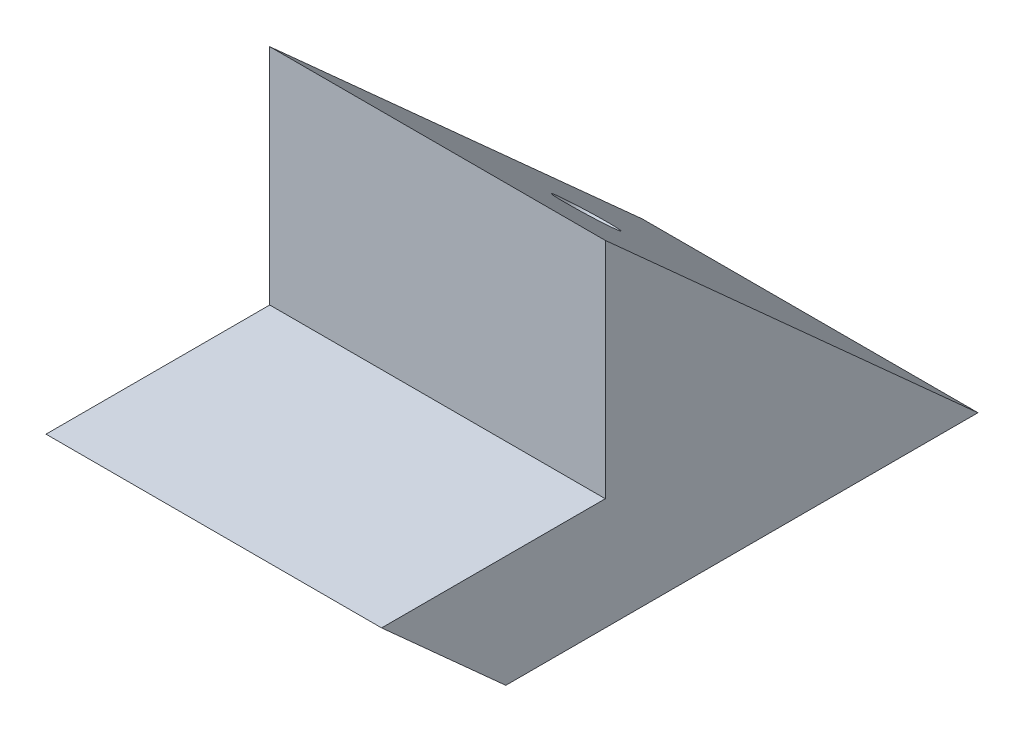
SolidWorks part; units mm, degrees
ref_plane "Front Plane" through (0, 0, 0) normal (0, 0, 1) x (1, 0, 0)
ref_plane "Top Plane" through (0, 0, 0) normal (0, 1, 0) x (1, 0, 0)
ref_plane "Right Plane" through (0, 0, 0) normal (1, 0, 0) x (0, 0, -1)
sketch "Esquisse1" plane through (0, 0, 0) normal (1, 0, 0) x (0, 0, -1)
  line L0 (0, 0) -> (33.3184, -30)
  line L1 (33.3184, -30) -> (-8.8939, -30)
  line L2 (-8.8939, -30) -> (-20, -20)
  line L3 (-20, -20) -> (0, -20)
  line L4 (0, -20) -> (0, 0)
  dimension "D1" = 42
  dimension "D2" = 42
  dimension "D3" = 20
  dimension "D4" = 20
  dimension "D5" = 10
extrude "Boss.-Extru.1" add sketch "Esquisse1" along normal blind 30
sketch "Esquisse2" plane through (0, 0, 0) normal (0, 0.7431, -0.6691) x (1, 0, 0)
  line L0 (15, 0) -> (15, 44.8343) construction
  line L1 (30, 0) -> (0, 0) construction
  line L2 (30, 44.8343) -> (0, 44.8343) construction
  line L3 (30, 22.4171) -> (0, 22.4171) construction
  line L4 (30, 44.8343) -> (30, 0) construction
  line L5 (0, 44.8343) -> (0, 0) construction
  circle A0 centre (15, 17.8672) radius 2.5
  point P14 (15, 17.8672)
extrude "Enlèv. mat.-Extru.1" cut sketch "Esquisse2" against normal through all
ref_plane "Plan1" through (0, -13.3766, 12.0444) normal (0, 0.7431, -0.6691) x (1, 0, 0)
sketch "Esquisse4" plane through (0, -13.3766, 12.0444) normal (0, 0.7431, -0.6691) x (1, 0, 0)
  circle A0 centre (15, 17.8672) radius 4.5
extrude "Enlèv. mat.-Extru.2" cut sketch "Esquisse4" against normal through all
